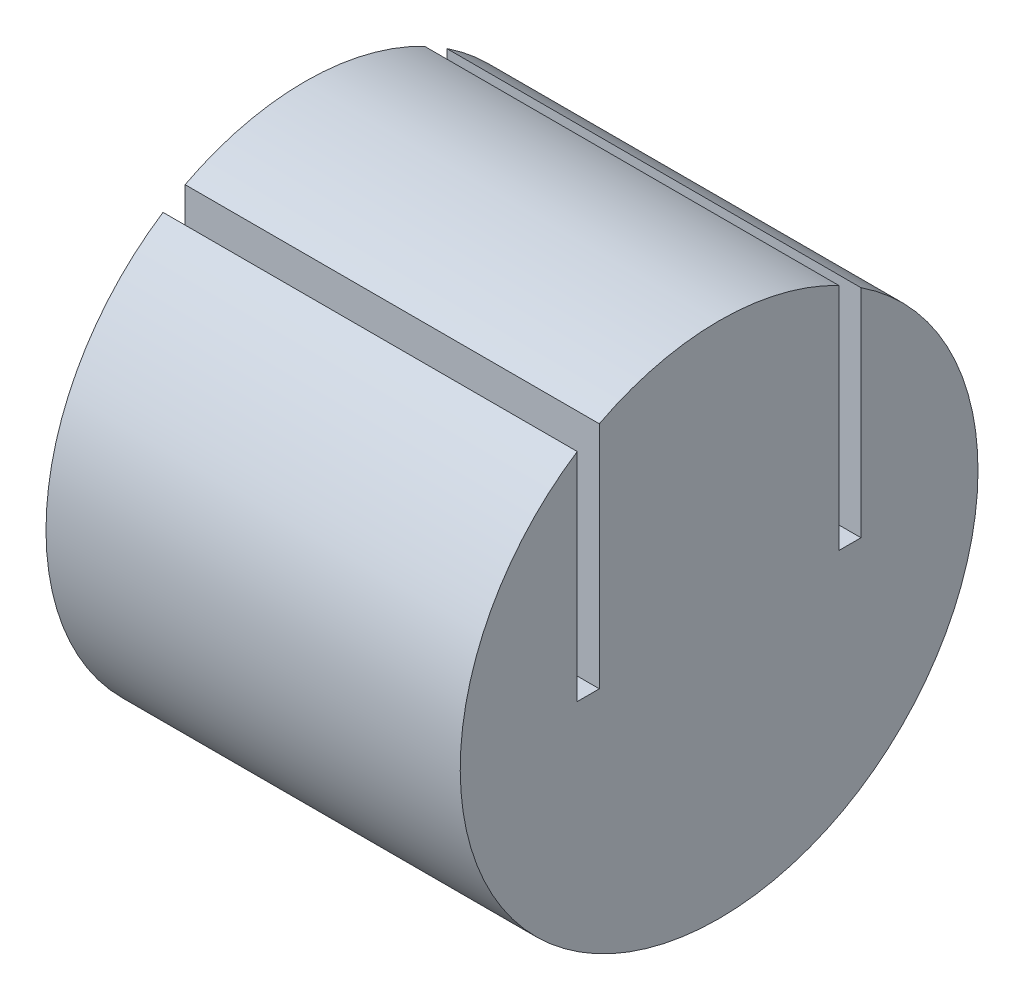
SolidWorks part; units mm, degrees
ref_plane "Front Plane" through (0, 0, 0) normal (0, 0, 1) x (1, 0, 0)
ref_plane "Top Plane" through (0, 0, 0) normal (0, 1, 0) x (1, 0, 0)
ref_plane "Right Plane" through (0, 0, 0) normal (1, 0, 0) x (0, 0, -1)
sketch "Sketch1" plane through (0, 0, 0) normal (1, 0, 0) x (0, 0, -1)
  line L0 (-4.4069, 0) -> (4.4069, 0) construction
  line L1 (-5.2197, 8.4442) -> (-4.4069, 8.4442)
  line L2 (-5.2197, 8.4442) -> (-5.2197, 0)
  line L3 (-5.2197, 0) -> (-4.4069, 0)
  line L4 (-4.4069, 8.4442) -> (-4.4069, 0)
  line L5 (4.4069, 0) -> (5.2197, 0)
  line L6 (4.4069, 0) -> (4.4069, 8.4442)
  line L7 (4.4069, 8.4442) -> (5.2197, 8.4442)
  line L8 (5.2197, 0) -> (5.2197, 8.4442)
  circle A0 centre (0, 0) radius 9.525
  point P11 (0, 0)
  dimension "D1" = 0.8128
  dimension "D3" = 19.05
  dimension "D2" = 8.8138
extrude "Boss-Extrude1" add sketch "Sketch1" along normal blind 15.24 contours L4 L0 L6 A0 | L0 L3 L2 A0 L8 L5
